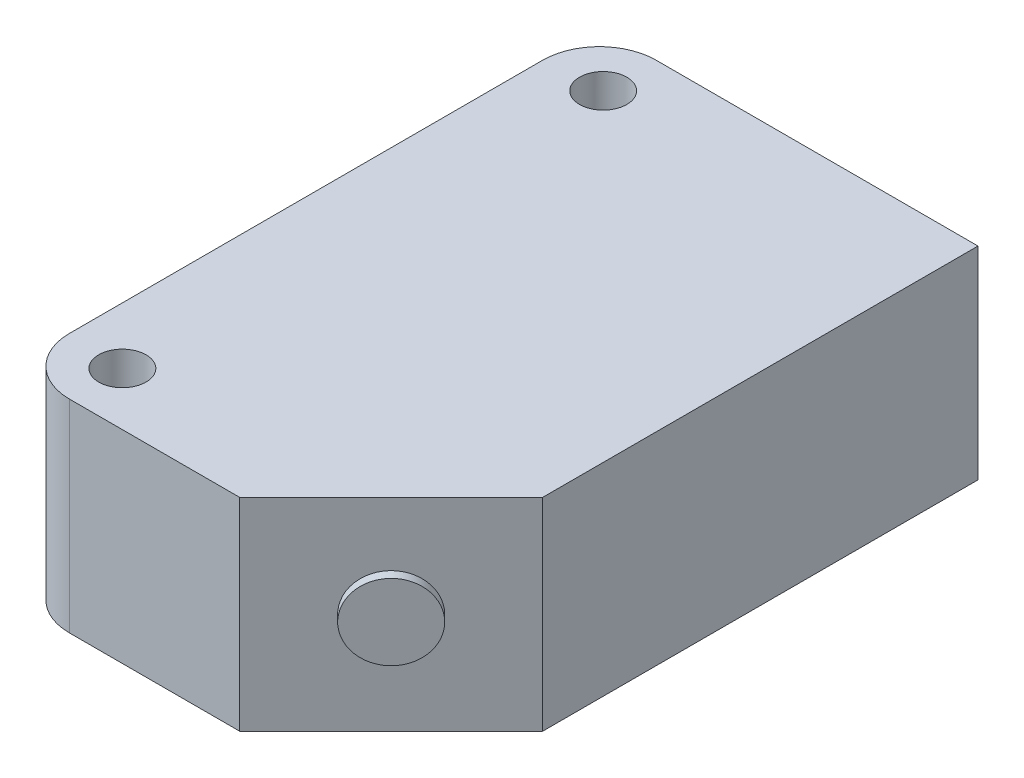
SolidWorks part; units mm, degrees
material "橡胶"
ref_plane "Front" through (0, 0, 0) normal (0, 0, 1) x (1, 0, 0)
ref_plane "Top" through (0, 0, 0) normal (0, 1, 0) x (1, 0, 0)
ref_plane "Right" through (0, 0, 0) normal (1, 0, 0) x (0, 0, -1)
sketch "草图1" plane through (0, 0, 0) normal (0, 1, 0) x (1, 0, 0)
  line L1 (10, 15.5) -> (-10, 15.5)
  line L2 (10, 15.5) -> (10, -15.5)
  line L3 (10, -15.5) -> (-10, -15.5)
  line L4 (-10, 15.5) -> (-10, -15.5)
  line L5 (10, 15.5) -> (-10, -15.5) construction
  line L6 (10, -15.5) -> (-10, 15.5) construction
  point P0 (0, 0)
  dimension "D1" = 31
  dimension "D2" = 20
extrude "凸台-拉伸1" add sketch "草图1" along normal blind 10.7
sketch "草图2" plane through (0, 10.7, 0) normal (0, 1, 0) x (1, 0, 0)
  line L0 (-7, 15.5) -> (-7, -15.5) construction
  line L1 (10, 15.5) -> (-10, 15.5) construction
  line L2 (-10, -15.5) -> (10, -15.5) construction
  line L3 (10, -15.5) -> (10, 15.5) construction
  line L4 (-7, 0) -> (0, 0) construction
  circle A0 centre (-7, 12.7) radius 1.25
  circle A2 centre (-7, -12.7) radius 1.25
  dimension "D2" = 2.5
  dimension "D3" = 25.4
  dimension "D1" = 17
extrude "切除-拉伸1" cut sketch "草图2" against normal blind 40.7
chamfer "倒角1" distance 8 angle 45 1 edges at (10, 5.35, 15.5)
sketch "草图3" plane through (8.75, 0, 8.75) normal (0.7071, 0, 0.7071) x (0.7071, 0, -0.7071)
  line L0 (-9.5459, 5.35) -> (1.7678, 5.35) construction
  line L1 (-9.5459, 0) -> (-9.5459, 10.7) construction
  line L2 (1.7678, 10.7) -> (1.7678, 0) construction
  circle A0 centre (-3.8891, 5.35) radius 2
extrude "凸台-拉伸2" add sketch "草图3" along normal blind 0.5
fillet "圆角1" radius 3 2 edges at (-10, 5.35, 15.5) (-10, 5.35, -15.5)
